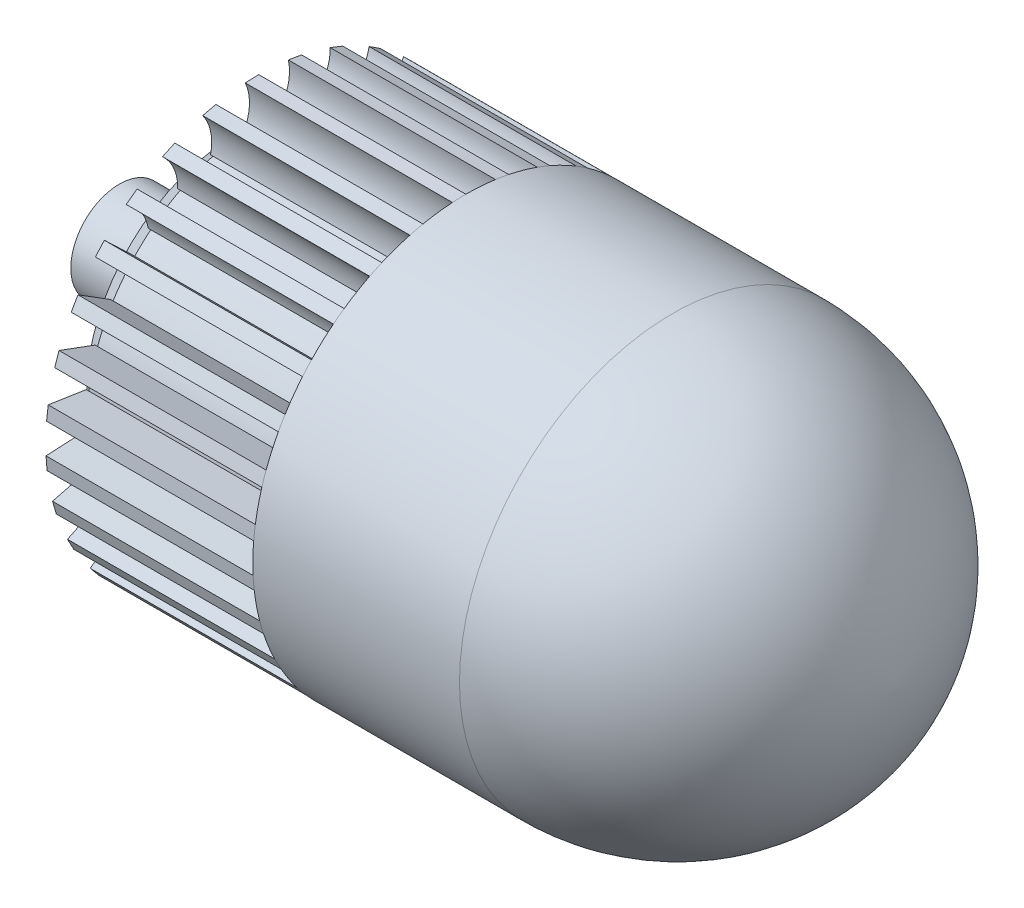
SolidWorks part; units mm, degrees
ref_plane "Front Plane" through (0, 0, 0) normal (0, 0, 1) x (1, 0, 0)
ref_plane "Top Plane" through (0, 0, 0) normal (0, 1, 0) x (1, 0, 0)
ref_plane "Right Plane" through (0, 0, 0) normal (1, 0, 0) x (0, 0, -1)
sketch "Sketch1" plane through (0, 0, 0) normal (0, 0, 1) x (1, 0, 0)
  line L0 (0, 0) -> (129.112, 0) construction
  line L1 (14.8357, 0) -> (14.8357, 6.3271)
  line L2 (14.8357, 6.3271) -> (29.6578, 6.3271)
  line L3 (29.6578, 6.3271) -> (29.6578, 19.0773)
  line L4 (29.6578, 19.0773) -> (33.3235, 22.743)
  line L5 (33.3235, 22.743) -> (60.0026, 22.743)
  line L6 (60.0026, 22.743) -> (60.0026, 27.7634)
  line L7 (60.0026, 27.7634) -> (86.9374, 27.7634)
  line L8 (14.8357, 0) -> (116.0405, 0)
  arc A0 (86.9374, 27.7634) -> (116.0405, 0) centre (86.9374, -1.372) cw
revolve "Revolve1" add sketch "Sketch1" angle 360 about L0
sketch "Sketch2" plane through (60.0026, 0, 0) normal (-1, 0, 0) x (0, 0, 1)
  line L0 (0, 22.743) -> (0, 27.7634)
  line L1 (0, 27.7634) -> (1.7531, 27.708)
  circle A0 centre (0, 0) radius 22.743 construction
  circle A1 centre (0, 0) radius 27.7634 construction
  arc A2 (0, 22.743) -> (1.7531, 22.6753) centre (0, 0) cw
  arc A3 (1.7531, 27.708) -> (1.7531, 22.6753) centre (7.2748, 25.1916) ccw
  circle A4 centre (0, 0) radius 22.743 construction
extrude "Boss-Extrude1" add sketch "Sketch2" along normal blind 27
pattern_circular "CirPattern1" count 31 over 360 about axis through (0, 0, 0) along (1, 0, 0) of "Boss-Extrude1"
